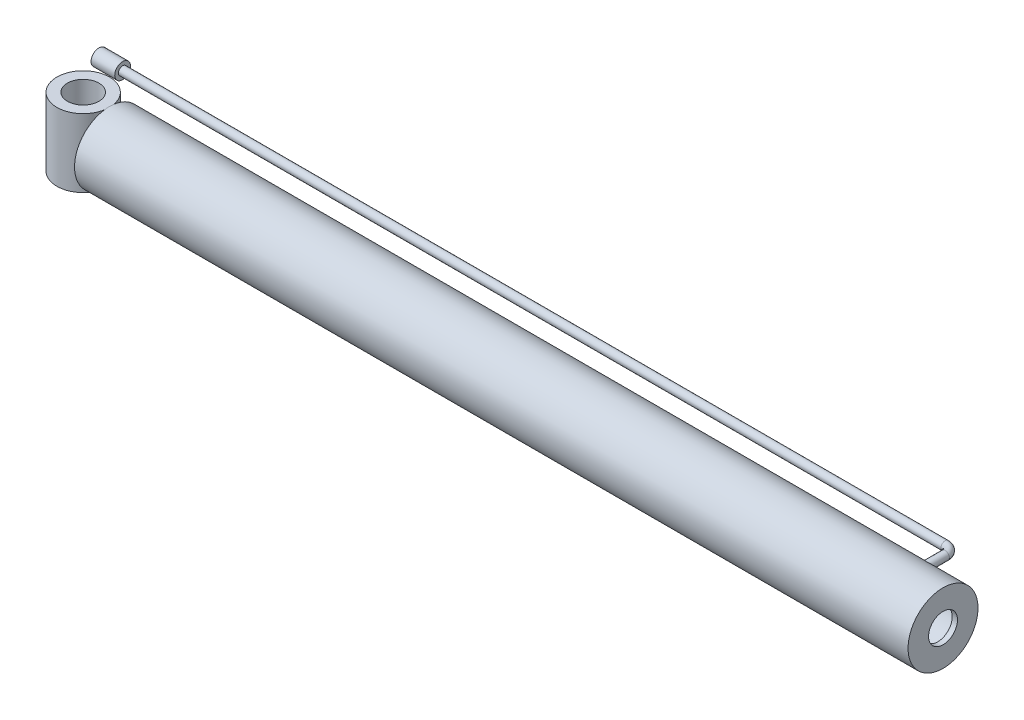
SolidWorks part; units mm, degrees
material "Q235"
ref_plane "前视基准面" through (0, 0, 0) normal (0, 0, 1) x (1, 0, 0)
ref_plane "上视基准面" through (0, 0, 0) normal (0, 1, 0) x (1, 0, 0)
ref_plane "右视基准面" through (0, 0, 0) normal (1, 0, 0) x (0, 0, -1)
sketch "草图1" plane through (0, 0, 0) normal (0, 0, 1) x (1, 0, 0)
  line L0 (0, 0) -> (30, 0) construction
  line L1 (30, -65) -> (30, 65)
  line L2 (30, 65) -> (50, 65)
  line L3 (30, -65) -> (50, -65)
  line L4 (0, 0) -> (0, 40.8031) construction
  line L5 (50, 65) -> (50, -65)
  point P6 (30, 0)
  dimension "D1" = 130
  dimension "D3" = 50
  dimension "D2" = 30
revolve "旋转1" add sketch "草图1" angle 360 about L4
ref_plane "基准面1" through (50, 0, 0) normal (1, 0, 0) x (0, 0, -1)
sketch "草图2" plane through (50, 0, 0) normal (1, 0, 0) x (0, 0, -1)
  circle A0 centre (0, 0) radius 40
  dimension "D1" = 80
extrude "凸台-拉伸1" add sketch "草图2" against normal up to body separate body
ref_plane "基准面2" through (75, 0, 0) normal (1, 0, 0) x (0, 0, -1)
sketch "草图3" plane through (75, 0, 0) normal (1, 0, 0) x (0, 0, -1)
  circle A0 centre (0, 0) radius 66.5
  dimension "D1" = 133
extrude "凸台-拉伸2" add sketch "草图3" against normal up to surface (25 mm away) separate body up to face at (50, 0, 0)
sketch "草图4" plane through (75, 0, 0) normal (1, 0, 0) x (0, 0, -1)
  circle A0 centre (0, 0) radius 55
  circle A1 centre (0, 0) radius 66.5
  circle A2 centre (0, 0) radius 66.5 construction
  dimension "D1" = 110
extrude "凸台-拉伸3" add sketch "草图4" along normal blind 1560
sketch "草图5" plane through (1635, 0, 0) normal (1, 0, 0) x (0, 0, -1)
  circle A0 centre (0, 0) radius 66.5 construction
  circle A1 centre (0, 0) radius 66.5
  circle A2 centre (0, 0) radius 27.5
  dimension "D1" = 55
extrude "凸台-拉伸4" add sketch "草图5" against normal blind 10
ref_plane "基准面3" through (0, 43, 0) normal (0, 1, 0) x (1, 0, 0)
ref_plane "基准面4" through (0, -43, 0) normal (0, 1, 0) x (1, 0, 0)
sketch "草图6" plane through (0, 43, 0) normal (0, 1, 0) x (1, 0, 0)
  line L0 (1560, 31.7372) -> (1560, 79)
  line L1 (1544, 95) -> (-65, 95)
  line L2 (1635, 66.5) -> (50, 66.5) construction
  line L3 (1635, 66.5) -> (50, 66.5) construction
  line L4 (1635, -66.5) -> (1635, 66.5) construction
  arc A0 (1560, 79) -> (1544, 95) centre (1544, 79) ccw
  dimension "D5" = 16
  dimension "D1" = 65
  dimension "D2" = 28.5
  dimension "D4" = 75
sketch "草图7" plane through (0, -43, 0) normal (0, 1, 0) x (1, 0, 0)
  line L0 (-65, 95) -> (69, 95)
  line L1 (1544, 95) -> (-65, 95) construction
  line L2 (85, 79) -> (85, 18.617)
  arc A0 (85, 79) -> (69, 95) centre (69, 79) ccw
  point P9 (85, 95)
  dimension "D2" = 16
  dimension "D1" = 85
ref_plane "基准面5" through (-65, -43, -95) normal (1, 0, 0) x (0, 0, -1)
sketch "草图8" plane through (-65, -43, -95) normal (1, 0, 0) x (0, 0, -1)
  circle A0 centre (0, 0) radius 8
  circle A2 centre (0, 0) radius 6
  dimension "D1" = 16
  dimension "D2" = 2
sweep "扫描1" add profiles "草图8" path "草图7"
ref_plane "基准面6" through (-65, 43, -95) normal (-1, 0, 0) x (0, 0, 1)
sketch "草图9" plane through (-65, 43, -95) normal (-1, 0, 0) x (0, 0, 1)
  line L0 (16, 0) -> (0, 0) construction
  circle A0 centre (0, 0) radius 8
  circle A1 centre (0, 0) radius 6
  dimension "D1" = 16
  dimension "D2" = 12
sweep "扫描2" add profiles "草图9" path "草图6"
sketch "草图10" plane through (-65, 0, 0) normal (-1, 0, 0) x (0, 0, 1)
  circle A0 centre (-95, 43) radius 15
  circle A1 centre (-95, -43) radius 15
  dimension "D1" = 30
  dimension "D2" = 30
extrude "凸台-拉伸5" add sketch "草图10" against normal blind 45
hole_wizard "M18 螺纹孔的螺纹孔钻头1" positions "草图11" profile "草图12" hole size "M18" standard "GB"
sketch "草图11" plane through (-65, 0, 0) normal (-1, 0, 0) x (0, 0, 1)
  point P0 (-95, -43)
  point P3 (-95, 43)
sketch "草图12" plane through (-65, -43, -95) normal (0, 1, 0) x (0, 0, 1)
  line L0 (0, 0) -> (0, 24.6567)
  line L1 (0, 24.6567) -> (7.75, 20)
  line L2 (7.75, 20) -> (7.75, 0)
  line L5 (7.75, 0) -> (0, 0)
  line L10 (0, 24.6567) -> (-7.75, 20) construction
  line L11 (0, -6.35) -> (0, 107.95) construction
  dimension "孔直径" = 15.5
  dimension "孔深度" = 20
  dimension "导头角度" = 118
